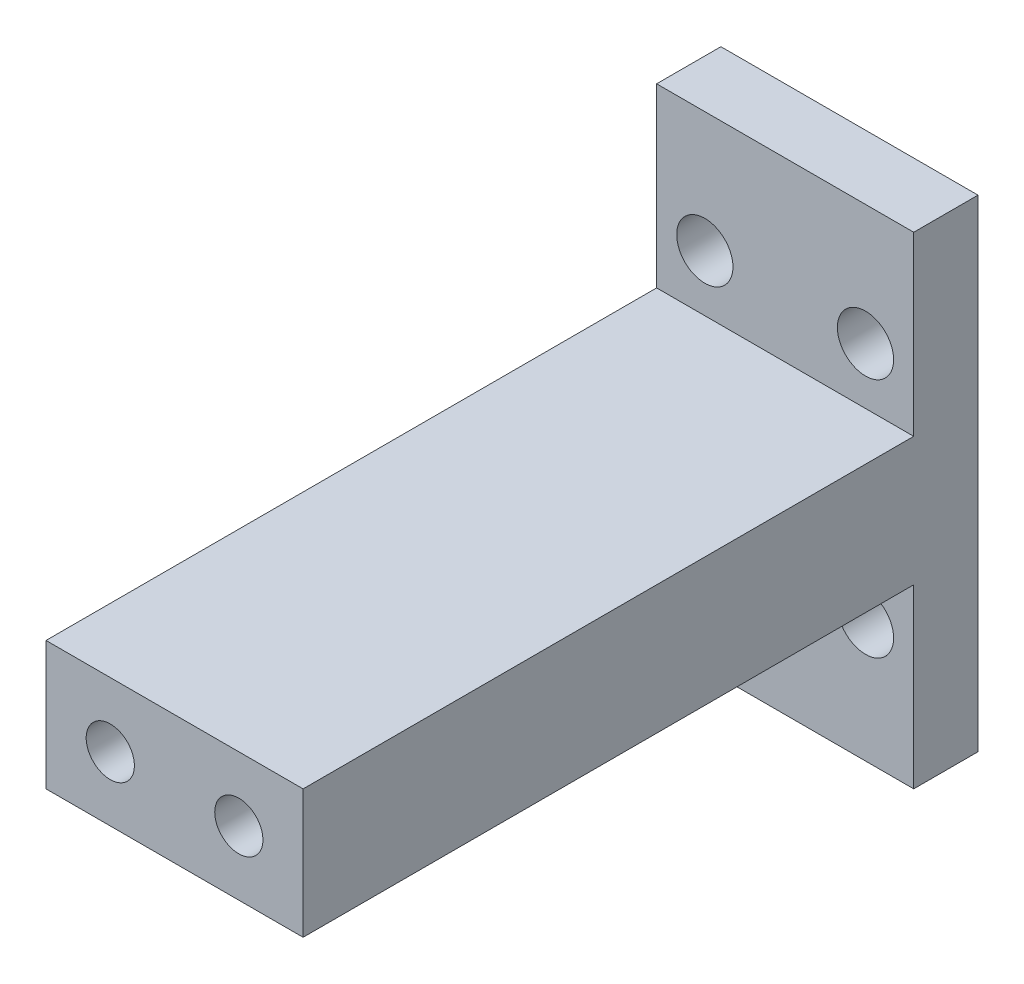
SolidWorks part; units mm, degrees
ref_plane "前视基准面" through (0, 0, 0) normal (0, 0, 1) x (1, 0, 0)
ref_plane "上视基准面" through (0, 0, 0) normal (0, 1, 0) x (1, 0, 0)
ref_plane "右视基准面" through (0, 0, 0) normal (1, 0, 0) x (0, 0, -1)
sketch "草图1" plane through (0, 0, 0) normal (0, 0, 1) x (1, 0, 0)
  line L0 (-3.0485, 0) -> (3.0485, 0) construction
  line L1 (-5, 7.5) -> (5, 7.5) construction
  line L2 (-5, 7.5) -> (-5, -7.5) construction
  line L3 (-5, -7.5) -> (5, -7.5) construction
  line L4 (5, 7.5) -> (5, -7.5) construction
  line L5 (-5, 7.5) -> (5, -7.5) construction
  line L6 (-5, -7.5) -> (5, 7.5) construction
  line L7 (0, 4.6712) -> (0, -4.6712) construction
  line L9 (-8, 15) -> (8, 15)
  line L10 (-8, 15) -> (-8, -15)
  line L11 (-8, -15) -> (8, -15)
  line L12 (8, 15) -> (8, -15)
  line L13 (-8, 15) -> (8, -15) construction
  line L14 (-8, -15) -> (8, 15) construction
  circle A0 centre (-5, 7.5) radius 1.75
  circle A1 centre (5, 7.5) radius 1.75
  circle A2 centre (5, -7.5) radius 1.75
  circle A3 centre (-5, -7.5) radius 1.75
  point P0 (0, 0)
  point P10 (0, 0)
  point P13 (0, 0)
  point P24 (0, 0)
  dimension "D3" = 3.5
  dimension "D1" = 15
  dimension "D2" = 10
  dimension "D6" = 30
  dimension "D7" = 16
extrude "凸台-拉伸3" add sketch "草图1" along normal blind 4
sketch "草图4" plane through (0, 0, 4) normal (0, 0, 1) x (1, 0, 0)
  line L0 (8, -15) -> (8, 15) construction
  line L1 (-8, 4) -> (8, 4)
  line L2 (-8, 4) -> (-8, -4)
  line L3 (-8, -4) -> (8, -4)
  line L4 (8, 4) -> (8, -4)
  line L5 (-8, 4) -> (8, -4) construction
  line L6 (-8, -4) -> (8, 4) construction
  point P0 (0, 0)
  dimension "D1" = 8
extrude "凸台-拉伸4" add sketch "草图4" along normal blind 38
sketch "草图6" plane through (0, 0, 42) normal (0, 0, 1) x (1, 0, 0)
  line L0 (0, 5.7875) -> (0, -5.7875) construction
  circle A0 centre (-4, 0) radius 1.5
  circle A1 centre (4, 0) radius 1.5
  point P4 (0, 0)
  dimension "D1" = 4
  dimension "D2" = 3
extrude "切除-拉伸1" cut sketch "草图6" against normal blind 10
